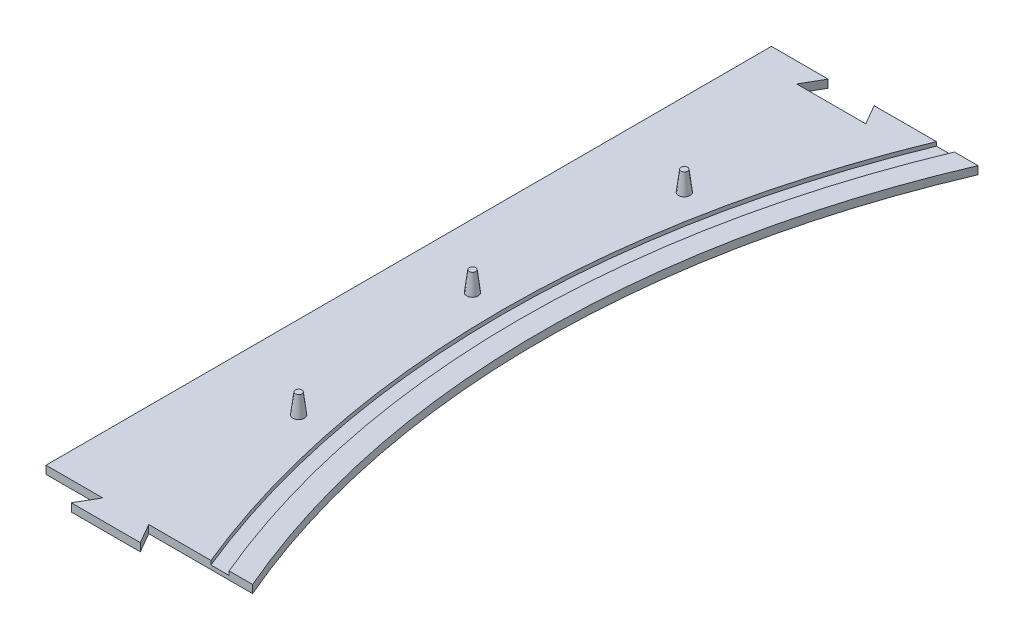
SolidWorks part; units mm, degrees
ref_plane "Front Plane" through (0, 0, 0) normal (0, 0, 1) x (1, 0, 0)
ref_plane "Top Plane" through (0, 0, 0) normal (0, 1, 0) x (1, 0, 0)
ref_plane "Right Plane" through (0, 0, 0) normal (1, 0, 0) x (0, 0, -1)
sketch "Sketch1" plane through (0, 0, 0) normal (0, 1, 0) x (1, 0, 0)
  line L7 (264, 0) -> (264, 131.98)
  line L9 (131.9796, 264) -> (0, 264)
  line L14 (131.9796, 264) -> (264, 131.98)
  line L15 (0, 264) -> (0, 0) construction
  line L16 (264, 109.3524) -> (186.6762, 186.6762) [skipped]
  line L17 (0, 0) -> (264, 0) construction
  line L18 (264, -131.9796) -> (131.98, -264)
  line L19 (-264, 0) -> (-264, -109.3524) [skipped]
  line L20 (-186.6762, 186.6762) -> (-264, 109.3524) [skipped]
  line L21 (-186.6762, -186.6762) -> (-109.3524, -264) [skipped]
  line L22 (0, -264) -> (109.3524, -264) [skipped]
  line L23 (186.6762, -186.6762) -> (264, -109.3524) [skipped]
  line L24 (264, -131.9796) -> (264, 0)
  line L25 (0, -264) -> (131.98, -264)
  line L26 (-131.9796, -264) -> (-264, -131.98)
  line L27 (-131.9796, -264) -> (0, -264)
  line L28 (-264, 0) -> (-264, -131.98)
  line L29 (-264, 131.9796) -> (-131.98, 264)
  line L30 (-264, 131.9796) -> (-264, 0)
  line L31 (0, 264) -> (-131.98, 264)
  arc A0 (264, 0) -> (0, 264) centre (0, 0) ccw construction
  point P33 (0, 0)
  dimension "D1" = 264
  dimension "D2" = 280
  dimension "D3" = 131.98
  dimension "D4" = 4
extrude "baseplate profile" add sketch "Sketch1" against normal blind 2
sketch "Sketch2" plane through (0, 0, 0) normal (0, 1, 0) x (1, 0, 0)
  line L0 (0, -248) -> (0, 248) construction
  circle A0 centre (0, 248) radius 1.45
  dimension "D2" = 2.9
  dimension "D1" = 496
extrude "M3 pins" add sketch "Sketch2" along normal blind 5 draft 7
sketch "center line" plane through (0, 0, 0) normal (0, 0, 1) x (1, 0, 0)
  line L0 (0, 0) -> (0, 200) construction
  dimension "D1" = 200
pattern_circular "CirPattern1" count 32 over 360 about axis through (0, 0, 0) along (0, 1, 0) of "M3 pins"
sketch "Sketch4" plane through (0, 0, 0) normal (0, 1, 0) x (1, 0, 0)
  line L0 (0, 0) -> (0, 201) construction
  line L1 (-9, 201) -> (9, 201) construction
  circle A0 centre (9, 201) radius 1
  circle A1 centre (-9, 201) radius 1
  point P5 (0, 201)
  dimension "D3" = 2
  dimension "D4" = 2
  dimension "D1" = 201
  dimension "D2" = 18
extrude "pillar pins" add sketch "Sketch4" along normal blind 5 draft 6
pattern_circular "CirPattern2" count 6 over 360 about axis through (0, 0, 0) along (0, 1, 0) of "pillar pins"
sketch "Sketch5" plane through (0, 0, 0) normal (0, 1, 0) x (1, 0, 0)
  line L0 (-193.0402, 193.0402) -> (193.0402, -193.0402) construction
  line L1 (-131.9796, -264) -> (131.98, -264) construction
  circle A0 centre (-193.0402, 193.0402) radius 3
  dimension "D3" = 6
  dimension "D1" = 546
  dimension "D2" = 45
extrude "M8 hole -1" add sketch "Sketch5" along normal blind 5 draft 12
pattern_circular "M8 -1 pattern" count 4 over 360 about axis through (0, 0, 0) along (0, 1, 0) of "M8 hole -1"
sketch "Sketch6" plane through (0, 0, 0) normal (0, 1, 0) x (1, 0, 0)
  line L0 (0, 0) -> (0, -324.5462) construction
  line L1 (0, 0) -> (-438.1399, 0) construction
  circle A0 centre (-125, -250) radius 3
  dimension "D1" = 6
  dimension "D2" = 125
  dimension "D3" = 250
extrude "M8 -2" add sketch "Sketch6" along normal blind 5 draft 12
pattern_circular "M8 -2 pattern" count 4 over 360 about axis through (0, 0, 0) along (0, 1, 0) of "M8 -2"
pattern_circular "M8 -3" count 2 over 36.9 about axis through (0, 0, 0) along (0, 1, 0) of "M8 -2 pattern", "M8 -2"
sketch "Sketch7" [suppressed] plane through (0, 0, 0) normal (0, 1, 0) x (1, 0, 0)
  line L1 (94.9211, 86.9806) -> (274.9211, 86.9806)
  line L2 (94.9211, 86.9806) -> (94.9211, -93.0194)
  line L3 (94.9211, -93.0194) -> (274.9211, -93.0194)
  line L4 (274.9211, 86.9806) -> (274.9211, -93.0194)
  dimension "D1" = 180
  dimension "D2" = 180
sketch "Sketch8" plane through (0, 0, 0) normal (0, 1, 0) x (1, 0, 0)
  line L0 (0, 0) -> (0, -180) construction
  line L1 (20, -230) -> (-20, -230)
  line L2 (20, -230) -> (20, -180)
  line L3 (20, -180) -> (-20, -180)
  line L4 (-20, -230) -> (-20, -180)
  line L5 (0, 0) -> (115.434, -199.9375)
  line L6 (0, 0) -> (-115.434, -199.9375)
  arc A0 (20, -230) -> (115.434, -199.9375) centre (0, 0) ccw
  arc A1 (-20, -230) -> (-115.434, -199.9375) centre (0, 0) cw
  point P7 (0, -180)
  dimension "D4" = 30
  dimension "D1" = 40
  dimension "D2" = 180
  dimension "D3" = 50
extrude "cut center" cut sketch "Sketch8" against normal through all contours L5 L0 L3 L2 A0 | L0 L6 A1 L4 L3
pattern_circular "CirPattern7" count 6 over 360 about axis through (0, 0, 0) along (0, 1, 0) of "cut center"
sketch "middle piece space " plane through (0, 0, 0) normal (0, 1, 0) x (1, 0, 0)
  line L0 (0, 0) -> (-200, 0) construction
  line L1 (91, 110) -> (-91, 110)
  line L2 (-110, 91) -> (-290, 91)
  line L3 (-110, 91) -> (-110, -91)
  line L4 (-110, -91) -> (-290, -91)
  line L5 (-290, 91) -> (-290, -91)
  line L6 (-110, 91) -> (-290, -91) construction
  line L7 (-110, -91) -> (-290, 91) construction
  line L8 (91, 110) -> (91, 290)
  line L9 (91, 290) -> (-91, 290)
  line L10 (-91, 110) -> (-91, 290)
  line L11 (110, -91) -> (110, 91)
  line L12 (110, -91) -> (290, -91)
  line L13 (290, -91) -> (290, 91)
  line L14 (110, 91) -> (290, 91)
  line L15 (-91, -110) -> (91, -110)
  line L16 (-91, -110) -> (-91, -290)
  line L17 (-91, -290) -> (91, -290)
  line L18 (91, -110) -> (91, -290)
  point P22 (0, 0)
  dimension "D1" = 182
  dimension "D2" = 200
  dimension "D3" = 180
  dimension "D4" = 4
sketch "Sketch11" plane through (0, 0, 0) normal (0, 1, 0) x (1, 0, 0)
  line L0 (-131.9796, -264) -> (131.98, -264) construction
  line L1 (-91, -91) -> (-264, -91)
  line L2 (-91, -91) -> (-91, -264)
  line L3 (-91, -264) -> (-264, -264)
  line L4 (-264, -91) -> (-264, -264)
  line L5 (-264, 131.9796) -> (-264, -131.98) construction
  line L6 (-110, -91) -> (-290, -91) construction
  line L7 (-91, -110) -> (-91, -290) construction
sketch "Sketch12" plane through (0, -2, 0) normal (0, -1, 0) x (1, 0, 0)
  line L0 (-110, 91) -> (-290, 91) construction
  line L1 (303.8847, 330.4144) -> (-306.2965, 330.4144)
  line L2 (303.8847, 330.4144) -> (303.8847, -333.6301)
  line L3 (303.8847, -333.6301) -> (-306.2965, -333.6301)
  line L4 (-306.2965, 330.4144) -> (-306.2965, -333.6301)
  line L5 (-200, 91) -> (-290, 91)
  line L6 (-200, 91) -> (-200, -91)
  line L7 (-200, -91) -> (-290, -91)
  line L8 (-290, 91) -> (-290, -91)
extrude "Cut-Extrude1" cut sketch "Sketch12" against normal blind 10
sketch "Sketch13" plane through (0, 0, 0) normal (0, 1, 0) x (1, 0, 0)
  line L0 (-110, -91) -> (-290, -91) construction
  line L1 (-252.6603, -96) -> (-235.3397, -96)
  line L2 (-235.3397, -96) -> (-244, -81)
  line L3 (-244, -81) -> (-252.6603, -96)
  line L4 (-264, 91) -> (-264, -91) construction
  circle A0 centre (-244, -91) radius 5 construction
  dimension "D1" = 10
  dimension "D2" = 20
extrude "Boss-Extrude1" add sketch "Sketch13" against normal up to surface (2 mm away) up to face at (-242.7612, -2, 0)
sketch "Sketch14" plane through (0, 0, 0) normal (0, 1, 0) x (1, 0, 0)
  line L0 (-110, 91) -> (-290, 91) construction
  line L1 (-252.6603, 86) -> (-235.3397, 86)
  line L2 (-235.3397, 86) -> (-244, 101)
  line L3 (-244, 101) -> (-252.6603, 86)
  line L4 (-264, 91) -> (-264, -91) construction
  circle A0 centre (-244, 91) radius 5 construction
  dimension "D1" = 10
  dimension "D2" = 20
extrude "Cut-Extrude2" cut sketch "Sketch14" against normal up to surface (2 mm away) contours L2 L3 L1 up to face at (-243.3806, -2, 46.75)
sketch "Sketch15" plane through (0, 0, 0) normal (0, 1, 0) x (1, 0, 0)
  circle A0 centre (0, 0) radius 240.5
  circle A1 centre (0, 0) radius 236.3
  dimension "D1" = 472.6
  dimension "D2" = 481
extrude "oring space" cut sketch "Sketch15" against normal blind 1
